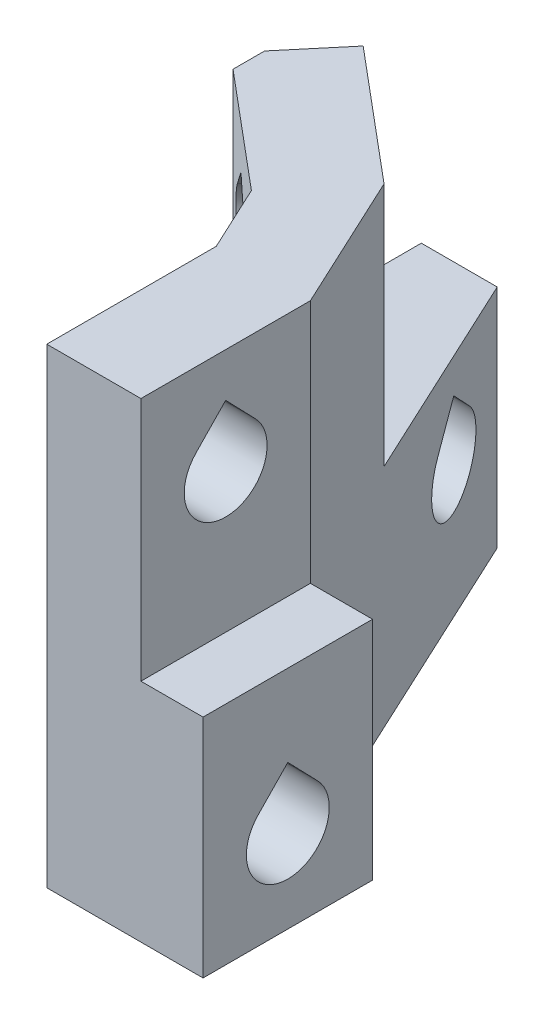
SolidWorks part; units mm, degrees
ref_plane "Front Plane" through (0, 0, 0) normal (0, 0, 1) x (1, 0, 0)
ref_plane "Top Plane" through (0, 0, 0) normal (0, 1, 0) x (1, 0, 0)
ref_plane "Right Plane" through (0, 0, 0) normal (1, 0, 0) x (0, 0, -1)
ref_plane "Plane1" through (0, -17, 0) normal (0, -1, 0) x (1, 0, 0)
sketch "Sketch1" plane through (0, -17, 0) normal (0, -1, 0) x (1, 0, 0)
  line L0 (-11.969, -12.5907) -> (-3.3, 6)
  line L1 (-3.3, 6) -> (-3.3, 15)
  line L2 (-3.3, 15) -> (-16, 15)
  line L3 (-16, 15) -> (-16, -12.5907)
  line L4 (-16, -12.5907) -> (-11.969, -12.5907)
extrude "Boss-Extrude1" add sketch "Sketch1" against normal blind 12
sketch "Sketch2" plane through (0, -5, 0) normal (0, 1, 0) x (-1, 0, 0)
  line L0 (16, 15) -> (16, -4.2678)
  line L1 (16, -4.2678) -> (13.6119, -7.1139)
  line L2 (13.6119, -7.1139) -> (6.7175, -1.3288)
  line L3 (6.7175, -1.3288) -> (3.3, 6)
  line L4 (3.3, 6) -> (3.3, 15)
  line L5 (3.3, 15) -> (16, 15)
extrude "Boss-Extrude2" add sketch "Sketch2" along normal blind 13
sketch "Sketch3" plane through (-3.3, 0, 0) normal (1, 0, 0) x (0, 0, -1)
  line L0 (-6, -5) -> (-6, -17)
  line L1 (-6, -17) -> (-15, -17)
  line L2 (-15, -17) -> (-15, -5)
  line L3 (-15, -5) -> (-6, -5)
extrude "Boss-Extrude3" add sketch "Sketch3" along normal blind 3.3
sketch "Sketch4" plane through (0, -17, 0) normal (0, -1, 0) x (1, 0, 0)
  line L0 (-16, -2.5907) -> (-8.3, 3.8704)
  line L1 (-8.3, 3.8704) -> (-8.3, 15)
  line L2 (-8.3, 15) -> (-16, 15)
  line L3 (-16, 15) -> (-16, -2.5907)
extrude "Cut-Extrude1" cut sketch "Sketch4" against normal through all
sketch "Sketch5" plane through (-8.3, 0, 0) normal (-1, 0, 0) x (0, 0, 1)
  line L0 (10.5, -9.333) -> (8.9175, -10.9718)
  line L1 (12.0825, -10.9718) -> (10.5, -9.333)
  arc A0 (8.9175, -10.9718) -> (12.0825, -10.9718) centre (10.5, -12.5) ccw
extrude "Cut-Extrude2" cut sketch "Sketch5" against normal through all
sketch "Sketch6" plane through (-8.3, 0, 0) normal (-1, 0, 0) x (0, 0, 1)
  line L0 (10.5, 5.667) -> (8.9175, 4.0282)
  line L1 (12.0825, 4.0282) -> (10.5, 5.667)
  arc A0 (8.9175, 4.0282) -> (12.0825, 4.0282) centre (10.5, 2.5) ccw
extrude "Cut-Extrude3" cut sketch "Sketch6" against normal through all
sketch "Sketch7" plane through (-5.3351, 0, 6.3582) normal (-0.6428, 0, 0.766) x (0.766, 0, 0.6428)
  line L0 (-10.5, 5.667) -> (-12.0826, 4.0282)
  line L1 (-8.9175, 4.0282) -> (-10.5, 5.667)
  arc A0 (-12.0826, 4.0282) -> (-8.9175, 4.0282) centre (-10.5, 2.5) ccw
extrude "Cut-Extrude4" cut sketch "Sketch7" against normal through all
sketch "Sketch8" plane through (-16, 0, 0) normal (-1, 0, 0) x (0, 0, 1)
  line L0 (-8.2698, -6.833) -> (-9.8523, -8.4718)
  line L1 (-6.6872, -8.4718) -> (-8.2698, -6.833)
  arc A0 (-9.8523, -8.4718) -> (-6.6872, -8.4718) centre (-8.2698, -10) ccw
extrude "Cut-Extrude5" cut sketch "Sketch8" against normal through all
chamfer "Chamfer1" distance 2.1296 angle 25 1 edges at (-8.3, -4.5, 3.8704)
